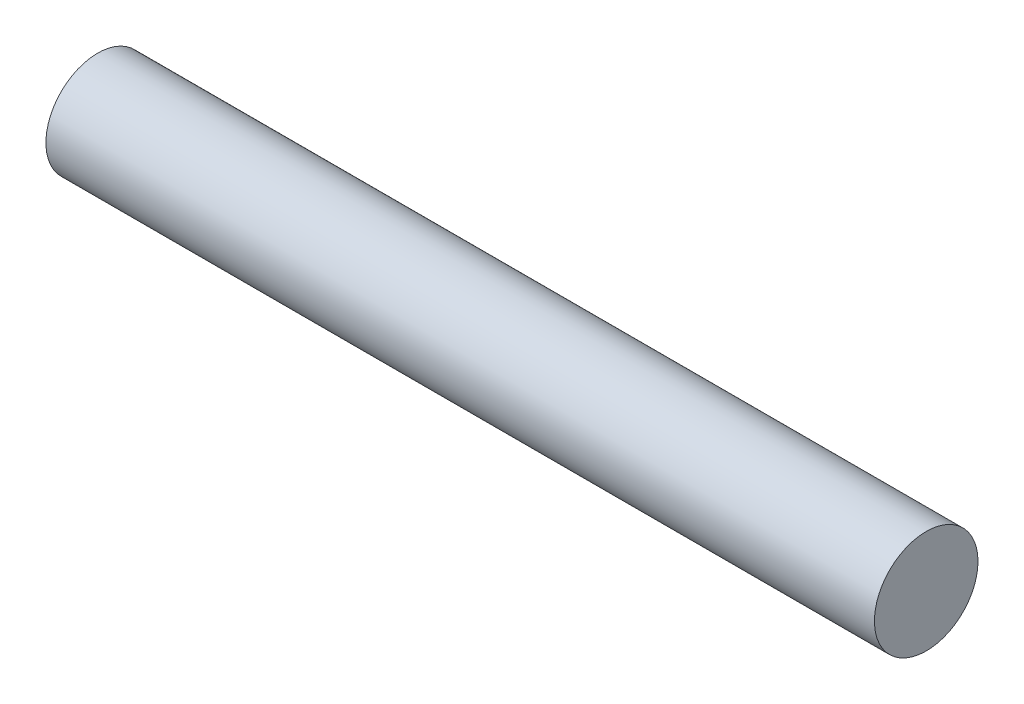
SolidWorks part; units mm, degrees
ref_plane "Front Plane" through (0, 0, 0) normal (0, 0, 1) x (1, 0, 0)
ref_plane "Top Plane" through (0, 0, 0) normal (0, 1, 0) x (1, 0, 0)
ref_plane "Right Plane" through (0, 0, 0) normal (1, 0, 0) x (0, 0, -1)
sketch "Sketch1" plane through (0, 0, 0) normal (1, 0, 0) x (0, 0, -1)
  circle A0 centre (0, 0) radius 3.175
  dimension "D1" = 6.35
extrude "Boss-Extrude1" add sketch "Sketch1" along normal mid plane 50.8
